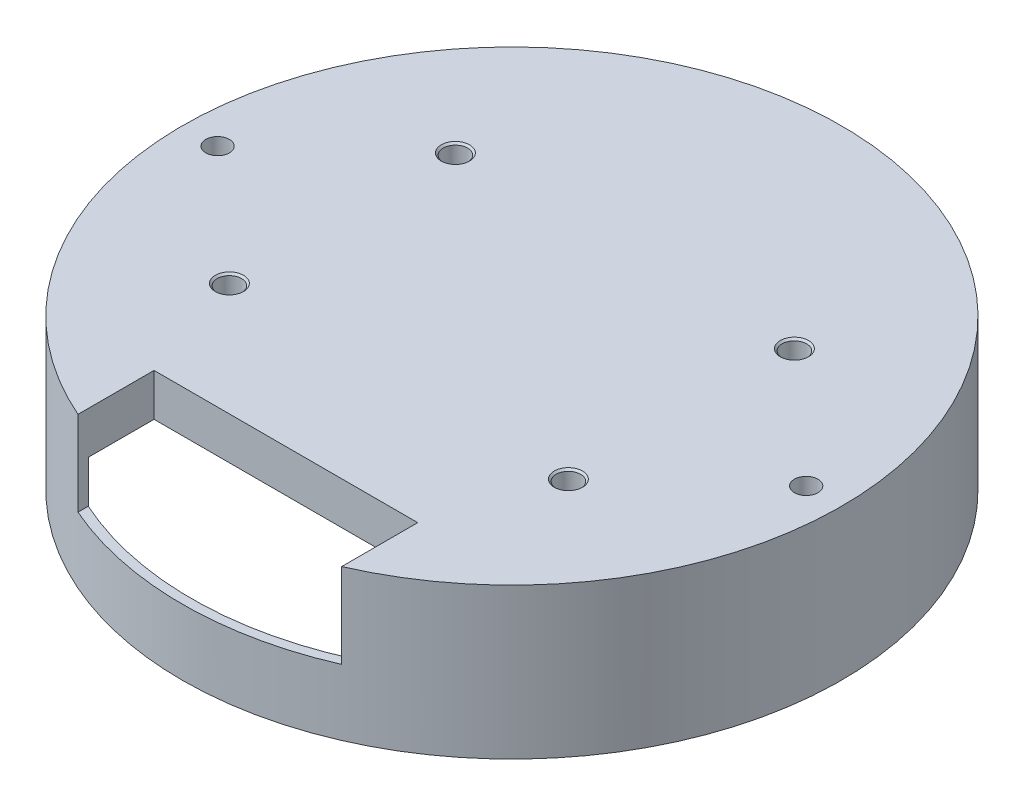
SolidWorks part; units mm, degrees
ref_plane "前基準面" through (0, 0, 0) normal (0, 0, 1) x (1, 0, 0)
ref_plane "上基準面" through (0, 0, 0) normal (0, 1, 0) x (1, 0, 0)
ref_plane "右基準面" through (0, 0, 0) normal (1, 0, 0) x (0, 0, -1)
sketch "草圖1" plane through (0, 0, 0) normal (0, 1, 0) x (1, 0, 0)
  circle A0 centre (0, 0) radius 35
  dimension "D1" = 70
extrude "填料-伸長1" add sketch "草圖1" along normal blind 16
sketch "草圖2" plane through (0, 0, 0) normal (0, -1, 0) x (1, 0, 0)
  circle A4 centre (0, 0) radius 34
  circle A5 centre (0, 0) radius 34
  dimension "D1" = 1
extrude "除料-伸長1" cut sketch "草圖2" against normal blind 11.5
sketch "草圖3" plane through (0, 0, 0) normal (0, 1, 0) x (1, 0, 0)
  line L0 (0, 0) -> (50000, 0) construction
  circle A0 centre (-31.25, 0) radius 1.25
  circle A1 centre (31.25, 0) radius 1.25
  dimension "D1" = 62.5
  dimension "D3" = 2.5
  dimension "D2" = 31.25
extrude "除料-伸長4" cut sketch "草圖3" along normal up to surface (16 mm away) up to face at (0, 16, 35)
sketch "草圖4" plane through (0, 16, 0) normal (0, 1, 0) x (1, 0, 0)
  line L0 (-14, -24) -> (14, -24)
  line L1 (14, -24) -> (14, -32.078)
  line L2 (-14, -24) -> (-14, -32.078)
  circle A0 centre (0, 0) radius 35 construction
  arc A1 (-14, -32.078) -> (14, -32.078) centre (0, 0) ccw
  point P2 (0, -24)
  point P3 (0, 35)
  dimension "D1" = 28
  dimension "D2" = 59
extrude "除料-伸長5" cut sketch "草圖4" against normal blind 9
sketch "草圖5" plane through (0, 16, 0) normal (0, 1, 0) x (1, 0, 0)
  line L1 (-18, 12) -> (18, 12) construction
  line L2 (-18, 12) -> (-18, -12) construction
  line L3 (-18, -12) -> (18, -12) construction
  line L4 (18, 12) -> (18, -12) construction
  line L5 (-18, 12) -> (18, -12) construction
  line L6 (-18, -12) -> (18, 12) construction
  circle A0 centre (-18, 12) radius 1.3
  circle A1 centre (18, 12) radius 1.3
  circle A2 centre (18, -12) radius 1.3
  circle A3 centre (-18, -12) radius 1.3
  point P0 (0, 0)
  dimension "D3" = 2.6
  dimension "D1" = 36
  dimension "D2" = 24
extrude "除料-伸長6" cut sketch "草圖5" against normal blind 2.5
chamfer "導角1" distance 0.2 4 edges at (18, 16, 13.3) (-18, 16, 13.3) (18, 16, -10.7) (-18, 16, -10.7)
